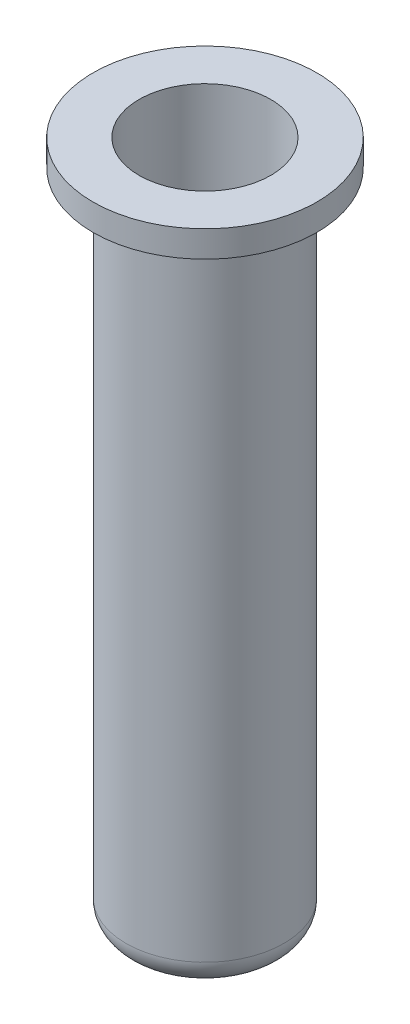
SolidWorks part; units mm, degrees
ref_plane "Front Plane" through (0, 0, 0) normal (0, 0, 1) x (1, 0, 0)
ref_plane "Top Plane" through (0, 0, 0) normal (0, 1, 0) x (1, 0, 0)
ref_plane "Right Plane" through (0, 0, 0) normal (1, 0, 0) x (0, 0, -1)
sketch "Sketch2" plane through (0, 0, 0) normal (0, 1, 0) x (1, 0, 0)
  circle A0 centre (0, 0) radius 3
  dimension "D1" = 6
extrude "Boss-Extrude1" add sketch "Sketch2" along normal blind 26
sketch "Sketch4" plane through (0, 26, 0) normal (0, 1, 0) x (1, 0, 0)
  circle A0 centre (0, 0) radius 2.5
  dimension "D1" = 5
extrude "Cut-Extrude1" cut sketch "Sketch4" against normal blind 14
fillet "Fillet3" radius 1 1 edges at (0, 0, 3)
sketch "Sketch5" plane through (0, 26, 0) normal (0, 1, 0) x (1, 0, 0)
  circle A0 centre (0, 0) radius 4.25
  circle A1 centre (0, 0) radius 3 construction
  circle A2 centre (0, 0) radius 3
  dimension "D1" = 8.5
extrude "Boss-Extrude2" add sketch "Sketch5" against normal blind 1
